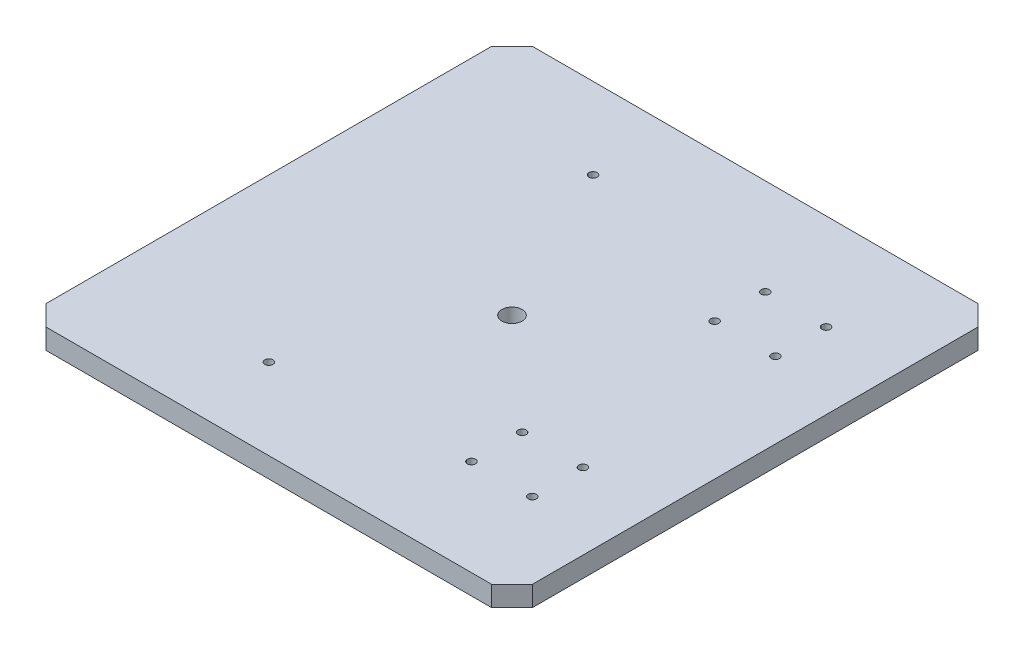
SolidWorks part; units mm, degrees
ref_plane "Front Plane" through (0, 0, 0) normal (0, 0, 1) x (1, 0, 0)
ref_plane "Top Plane" through (0, 0, 0) normal (0, 1, 0) x (1, 0, 0)
ref_plane "Right Plane" through (0, 0, 0) normal (1, 0, 0) x (0, 0, -1)
sketch "Sketch1" plane through (0, 0, 0) normal (0, 1, 0) x (1, 0, 0)
  line L1 (0, 0) -> (304.8, 0)
  line L2 (0, 0) -> (0, 304.8)
  line L3 (0, 304.8) -> (304.8, 304.8)
  line L4 (304.8, 0) -> (304.8, 304.8)
  dimension "D1" = 304.8
  dimension "D2" = 304.8
extrude "Boss-Extrude1" add sketch "Sketch1" along normal blind 12.7
chamfer "Chamfer1" distance 12.7 angle 45 4 edges at (0, 6.35, 0) (0, 6.35, -304.8) (304.8, 6.35, -304.8) (304.8, 6.35, 0)
hole_wizard "1/4-20 Tapped Hole1" positions "Sketch2" profile "Sketch3" tap size "1/4-20" standard "ANSI Inch" end condition through all
sketch "Sketch2" plane through (0, 12.7, 0) normal (0, 1, 0) x (1, 0, 0)
  line L0 (304.8, 152.4) -> (0, 152.4) construction
  line L1 (304.8, 12.7) -> (304.8, 292.1) construction
  line L2 (0, 292.1) -> (0, 12.7) construction
  point P0 (101.6, 50.8)
  point P2 (101.6, 254)
  point P14 (0, 0)
  dimension "D1" = 203.2
  dimension "D2" = 101.6
sketch "Sketch3" plane through (101.6, 12.7, -50.8) normal (1, 0, 0) x (0, 0, 1)
  line L0 (0, 0) -> (0, 12.7)
  line L1 (0, 12.7) -> (2.5527, 12.7)
  line L2 (2.5527, 12.7) -> (2.5527, 0)
  line L5 (2.5527, 0) -> (0, 0)
  line L11 (0, -6.35) -> (0, 107.95) construction
  dimension "Thru Tap Drill Dia." = 5.1054
  dimension "Thru Tap Drill Depth" = 12.7
cosmetic thread "Hole Thread1" parameters "D2"=6.35
cosmetic thread "Hole Thread2" parameters "D2"=6.35
sketch "Sketch4" plane through (0, 12.7, 0) normal (0, 1, 0) x (1, 0, 0)
  line L0 (0, 152.4) -> (304.8, 152.4) construction
  line L1 (0, 292.1) -> (0, 12.7) construction
  line L2 (304.8, 12.7) -> (304.8, 292.1) construction
  circle A0 centre (152.4, 152.4) radius 6.35
  point P8 (0, 0)
  dimension "D1" = 12.7
extrude "Cut-Extrude1" cut sketch "Sketch4" against normal through all and the other way through all
hole_wizard "1/4-20 Tapped Hole2" positions "Sketch5" profile "Sketch6" tap size "1/4-20" standard "ANSI Inch" end condition through all
sketch "Sketch5" plane through (0, 12.7, 0) normal (0, 1, 0) x (1, 0, 0)
  line L0 (304.8, 12.7) -> (304.8, 292.1) construction
  line L1 (219.075, 244.475) -> (257.175, 244.475) construction
  line L4 (304.8, 152.4) -> (0, 152.4) construction
  line L5 (0, 292.1) -> (0, 12.7) construction
  line L8 (257.175, 244.475) -> (257.175, 212.725) construction
  line L11 (257.175, 228.6) -> (219.075, 228.6) construction
  line L14 (257.175, 212.725) -> (219.075, 212.725) construction
  line L17 (219.075, 244.475) -> (219.075, 212.725) construction
  point P0 (257.175, 244.475)
  point P2 (219.075, 244.475)
  point P20 (257.175, 212.725)
  point P22 (219.075, 212.725)
  point P52 (0, 0)
  point P59 (0, 0)
  point P60 (257.175, 92.075)
  point P61 (219.075, 92.075)
  point P62 (257.175, 60.325)
  point P63 (219.075, 60.325)
  dimension "D1" = 38.1
  dimension "D2" = 47.625
  dimension "D3" = 31.75
  dimension "D4" = 76.2
sketch "Sketch6" plane through (257.175, 12.7, -244.475) normal (1, 0, 0) x (0, 0, 1)
  line L0 (0, 0) -> (0, 12.7)
  line L1 (0, 12.7) -> (2.5527, 12.7)
  line L2 (2.5527, 12.7) -> (2.5527, 0)
  line L5 (2.5527, 0) -> (0, 0)
  line L11 (0, -6.35) -> (0, 107.95) construction
  dimension "Thru Tap Drill Dia." = 5.1054
  dimension "Thru Tap Drill Depth" = 12.7
cosmetic thread "Hole Thread3" parameters "D2"=6.35
cosmetic thread "Hole Thread4" parameters "D2"=6.35
cosmetic thread "Hole Thread5" parameters "D2"=6.35
cosmetic thread "Hole Thread6" parameters "D2"=6.35
cosmetic thread "Hole Thread7" parameters "D2"=6.35
cosmetic thread "Hole Thread8" parameters "D2"=6.35
cosmetic thread "Hole Thread9" parameters "D2"=6.35
cosmetic thread "Hole Thread10" parameters "D2"=6.35
